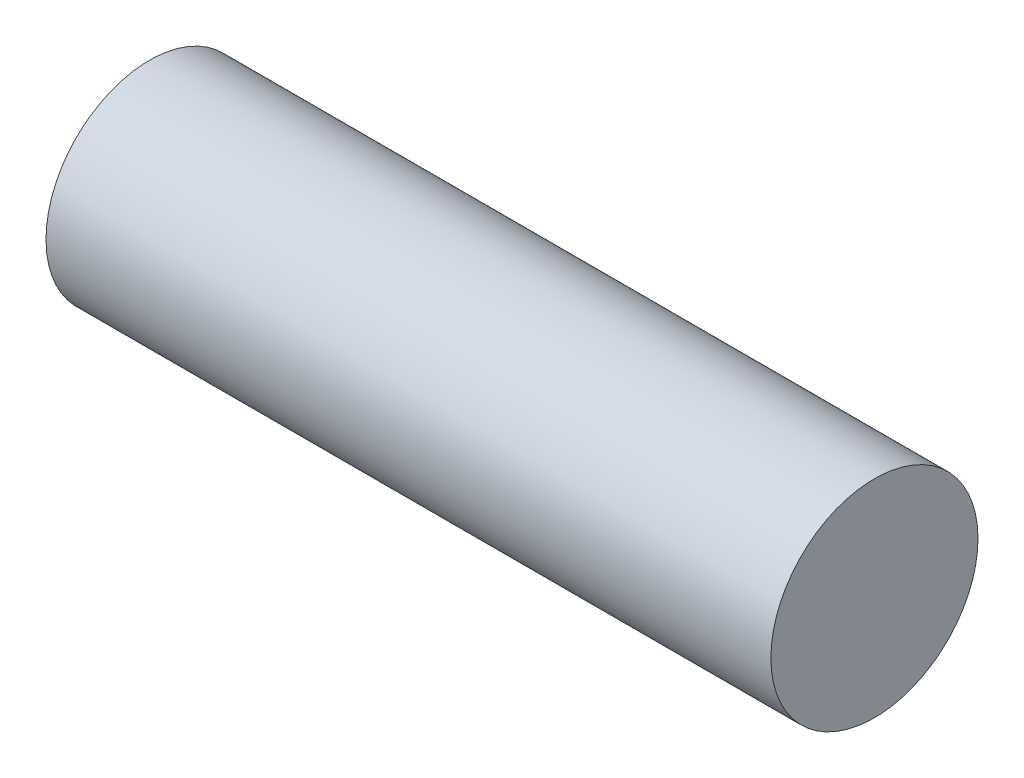
SolidWorks part; units mm, degrees
ref_plane "Plan de face" through (0, 0, 0) normal (0, 0, 1) x (1, 0, 0)
ref_plane "Plan de dessus" through (0, 0, 0) normal (0, 1, 0) x (1, 0, 0)
ref_plane "Plan de droite" through (0, 0, 0) normal (1, 0, 0) x (0, 0, -1)
sketch "Esquisse1" plane through (0, 0, 0) normal (0, 0, 1) x (1, 0, 0)
  line L0 (14, 0) -> (-14, 0)
  line L1 (0, 0) -> (0, 4)
  line L2 (-14, 4) -> (14, 4)
  line L3 (14, 4) -> (14, 0)
  line L4 (-14, 4) -> (-14, 0)
  dimension "D1" = 14
  dimension "D2" = 4
revolve "Révolution1" add sketch "Esquisse1" angle 360 about L0
